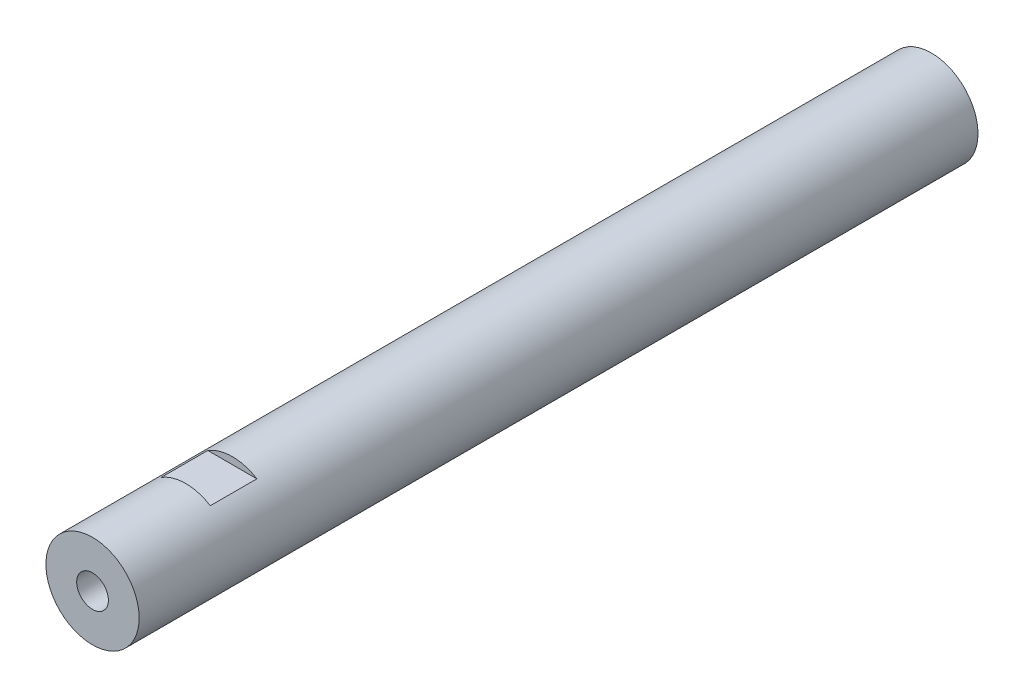
SolidWorks part; units mm, degrees
other "Detailelement1"
other "Detailelement2"
other "Detailelement3"
other "Detailelement4"
other "Detailelement7"
material "1.4301 (X5CrNi18-10)"
ref_plane "Ebene1" through (0, 0, 0) normal (0, 0, 1) x (1, 0, 0)
ref_plane "Ebene2" through (0, 0, 0) normal (0, 1, 0) x (1, 0, 0)
ref_plane "Ebene3" through (0, 0, 0) normal (1, 0, 0) x (0, 0, -1)
ref_plane "Ebene4" through (0, 0, 70) normal (0, 0, 1) x (1, 0, 0)
sketch "Skizze1" plane through (0, 0, 0) normal (0, 0, 1) x (1, 0, 0)
  circle A0 centre (0, 0) radius 10
  dimension "D1" = 20
extrude "Basis-Linear austragen" add sketch "Skizze1" along normal mid plane 180
hole_wizard "M8 Gewindebohrung1" positions "Skizze3" profile "Skizze2" tap size "M8" standard "Gabler-Normteile"
sketch "Skizze3" plane through (0, 0, 90) normal (0, 0, 1) x (1, 0, 0)
  line L0 (0, 81.4132) -> (0, -82.4321) construction
  line L2 (-36.0704, 0) -> (43.203, 0) construction
  point P0 (0, 0)
  point P12 (0, 0)
sketch "Skizze2" plane through (0, 0, 90) normal (1, 0, 0) x (0, -1, 0)
  line L0 (0, 0) -> (0, 24.2929)
  line L1 (0, 24.2929) -> (3.4, 22.25)
  line L2 (3.4, 22.25) -> (3.4, 0)
  line L5 (3.4, 0) -> (0, 0)
  line L10 (0, 24.2929) -> (-3.4, 22.25) construction
  line L11 (0, -6.35) -> (0, 107.95) construction
  dimension "Bohrerdurchmesser" = 6.8
  dimension "Bohrungstiefe" = 22.25
  dimension "Spitzenwinkel" = 118
cosmetic thread "Bohrungsgewinde3" parameters "D1"=16, "D2"=8
cosmetic thread "Bohrungsgewinde4" parameters "D1"=16, "D2"=8
sketch "Skizze5" plane through (0, 0, 70) normal (0, 0, 1) x (1, 0, 0)
  line L1 (-5.2678, 8.5) -> (5.2678, 8.5)
  line L2 (-5.2678, 8.5) -> (-5.2678, 10)
  line L3 (-5.2678, 10) -> (5.2678, 10)
  line L4 (5.2678, 8.5) -> (5.2678, 10)
  line L5 (-5.2678, -8.5) -> (5.2678, -8.5)
  line L6 (-5.2678, -8.5) -> (-5.2678, -10)
  line L7 (-5.2678, -10) -> (5.2678, -10)
  line L8 (5.2678, -8.5) -> (5.2678, -10)
  circle A0 centre (0, 0) radius 10 construction
  dimension "D1" = 17
extrude "Schnitt-Linear austragen1" cut sketch "Skizze5" against normal blind 10
mirror "Spiegeln1" about plane through (0, 0, 0) normal (0, 0, 1) of "M8 Gewindebohrung1"
